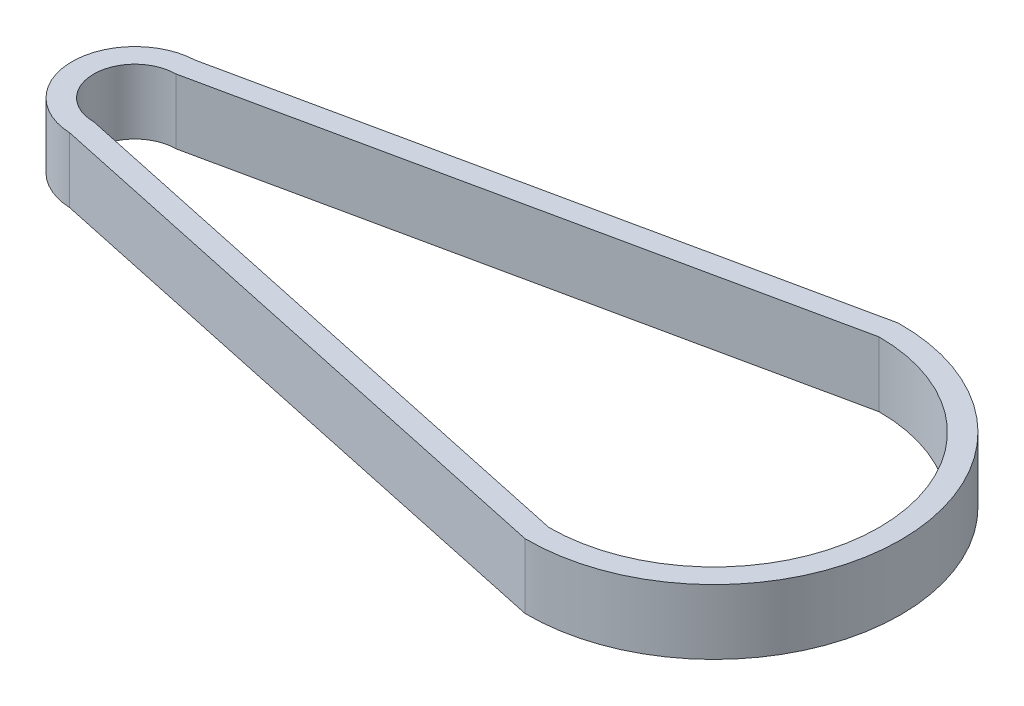
SolidWorks part; units mm, degrees
ref_plane "Front Plane" through (0, 0, 0) normal (0, 0, 1) x (1, 0, 0)
ref_plane "Top Plane" through (0, 0, 0) normal (0, 1, 0) x (1, 0, 0)
ref_plane "Right Plane" through (0, 0, 0) normal (1, 0, 0) x (0, 0, -1)
sketch "Sketch1" plane through (0, 0, 0) normal (0, 1, 0) x (1, 0, 0)
  line L0 (0, 9.55) -> (133.995, 38.195)
  line L1 (0, -9.55) -> (133.995, -38.195)
  line L2 (-0.5832, -14.5383) -> (133.4505, -43.1916)
  line L3 (-0.5832, 14.5383) -> (133.4505, 43.1916)
  arc A0 (0, 9.55) -> (0, -9.55) centre (0, 0) ccw
  arc A1 (133.995, -38.195) -> (133.995, 38.195) centre (133.995, 0) ccw
  arc A2 (133.4505, -43.1916) -> (133.4505, 43.1916) centre (133.995, 0) ccw
  arc A3 (-0.5832, 14.5383) -> (-0.5832, -14.5383) centre (0, 0) ccw
  dimension "D1" = 19.1
  dimension "D2" = 76.39
  dimension "D3" = 133.995
  dimension "D4" = 5
extrude "Boss-Extrude1" add sketch "Sketch1" along normal blind 15
